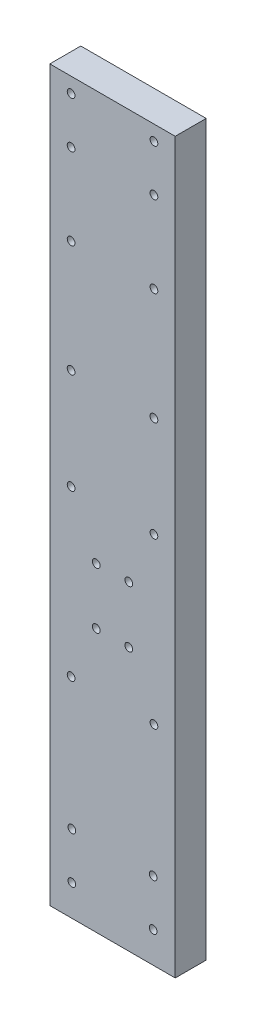
SolidWorks part; units mm, degrees
ref_plane "Front Plane" through (0, 0, 0) normal (0, 0, 1) x (1, 0, 0)
ref_plane "Top Plane" through (0, 0, 0) normal (0, 1, 0) x (1, 0, 0)
ref_plane "Right Plane" through (0, 0, 0) normal (1, 0, 0) x (0, 0, -1)
sketch "Sketch3" plane through (0, 0, 0) normal (0, 0, 1) x (1, 0, 0)
  line L0 (0, 94.0064) -> (0, -0.1536)
  line L1 (16.2, 94.0064) -> (16.2, -0.1536)
  line L2 (0, -0.1536) -> (16.2, -0.1536)
  line L4 (0, 94.0064) -> (16.2, 94.0064)
  line L5 (0, 12.3464) -> (16.2, 12.3464) construction
  line L6 (0, 58.6064) -> (16.2, 58.6064) construction
  line L26 (0, 50.6064) -> (16.2, 50.6064) construction
  line L27 (0, 24.3464) -> (16.2, 24.3464) construction
  line L30 (0, 78.0614) -> (16.2, 78.0614) construction
  line L32 (0, 84.0614) -> (16.2, 84.0614) construction
  circle A0 centre (6, 33.8464) radius 0.5
  circle A1 centre (10.2, 33.8464) radius 0.5
  circle A2 centre (2.75, 86.0614) radius 0.5
  circle A3 centre (10.2, 41.1664) radius 0.5
  circle A4 centre (13.45, 48.1064) radius 0.5
  circle A5 centre (2.75, 92.0614) radius 0.5
  circle A6 centre (13.45, 86.0614) radius 0.5
  circle A7 centre (2.75, 61.1064) radius 0.5
  circle A16 centre (2.85, 9.8464) radius 0.5
  circle A17 centre (13.35, 9.8464) radius 0.5
  circle A18 centre (13.35, 3.8464) radius 0.5
  circle A19 centre (2.85, 3.8464) radius 0.5
  circle A20 centre (13.45, 61.1064) radius 0.5
  circle A21 centre (2.75, 75.5614) radius 0.5
  circle A22 centre (13.45, 26.8464) radius 0.5
  circle A23 centre (13.45, 75.5614) radius 0.5
  circle A24 centre (13.45, 92.0614) radius 0.5
  circle A25 centre (2.75, 26.8464) radius 0.5
  circle A26 centre (6, 41.1064) radius 0.5
  circle A27 centre (2.75, 48.1064) radius 0.5
  dimension "D1" = 2.5
  dimension "D2" = 9.5
  dimension "D32" = 6
  dimension "D33" = 6
  dimension "D3" = 2.5
  dimension "D4" = 9.5
  dimension "D5" = 6
  dimension "D6" = 2.75
  dimension "D7" = 2.75
  dimension "D8" = 6
  dimension "D9" = 2.5
  dimension "D10" = 2.5
  dimension "D11" = 9.5
  dimension "D12" = 9.44
  dimension "D13" = 2.75
  dimension "D14" = 6
  dimension "D15" = 2.75
  dimension "D16" = 6
  dimension "D17" = 12
  dimension "D18" = 2.5
  dimension "D19" = 4
  dimension "D20" = 6
  dimension "D21" = 6
  dimension "D22" = 4
  dimension "D23" = 2.85
  dimension "D24" = 2.85
  dimension "D25" = 26.26
  dimension "D26" = 16.2
  dimension "D27" = 8
  dimension "D28" = 2.5
  dimension "D29" = 2.5
  dimension "D30" = 2.75
  dimension "D31" = 2.75
  dimension "D34" = 2.5
  dimension "D35" = 2.5
  dimension "D36" = 2.75
  dimension "D37" = 2.75
  dimension "D38" = 19.455
  dimension "D39" = 6
  dimension "D40" = 2
  dimension "D41" = 2
  dimension "D42" = 2.75
  dimension "D43" = 2.75
  dimension "D44" = 2.5
  dimension "D46" = 2.75
  dimension "D47" = 2.75
  dimension "D48" = 9.945
extrude "Boss-Extrude3" add sketch "Sketch3" along normal blind 4
equation "\"D25@Sketch3\"= \"HL@parametersSketch@prostheticParameters.SLDPRT\" * 0.196 - 4 - 6'Index PIP length"
equation "\"D26@Sketch3\"= \"fingerWidth@parametersSketch@prostheticParameters.SLDPRT\"'Index Width"
equation "\"D38@Sketch3\"= \"HL@parametersSketch@prostheticParameters.SLDPRT\" * 0.143 - 3 - 4 'Index MIP Length"
equation "\"D48@Sketch3\"= \"HL@parametersSketch@prostheticParameters.SLDPRT\" * 0.097 - 3 - 5'Index DIP Length - Gap Fingertip"
